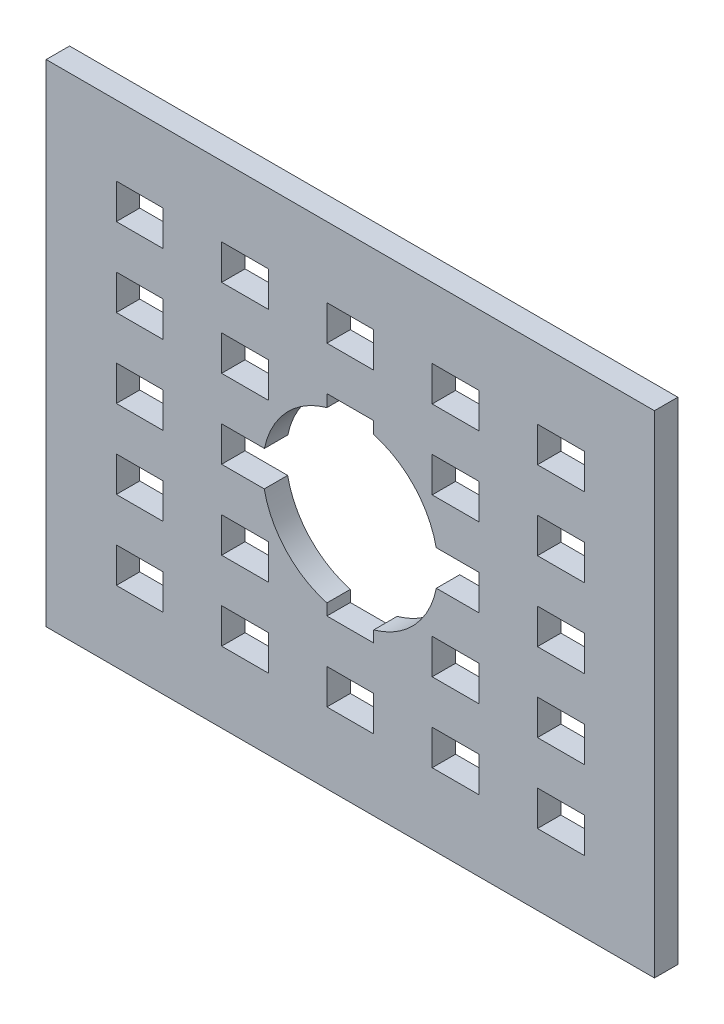
SolidWorks part; units mm, degrees
ref_plane "Front Plane" through (0, 0, 0) normal (0, 0, 1) x (1, 0, 0)
ref_plane "Top Plane" through (0, 0, 0) normal (0, 1, 0) x (1, 0, 0)
ref_plane "Right Plane" through (0, 0, 0) normal (1, 0, 0) x (0, 0, -1)
sketch "Sketch1" plane through (0, 0, 0) normal (0, 1, 0) x (1, 0, 0)
  line L1 (-13, -0.5) -> (13, -0.5)
  line L2 (-13, -0.5) -> (-13, 0.5)
  line L3 (-13, 0.5) -> (13, 0.5)
  line L4 (13, -0.5) -> (13, 0.5)
  line L5 (-13, -0.5) -> (13, 0.5) construction
  line L6 (-13, 0.5) -> (13, -0.5) construction
  point P0 (0, 0)
  dimension "D1" = 26
  dimension "D2" = 1
extrude "Boss-Extrude1" add sketch "Sketch1" along normal blind 21
sketch "Sketch2" plane through (0, 0, 0.5) normal (0, 0, 1) x (1, 0, 0)
  line L0 (-13, 10.5) -> (-10, 10.5) construction
  line L1 (-5.5, 18) -> (-3.5, 18)
  line L2 (-13, 21) -> (-13, 0) construction
  line L3 (0, 21) -> (0, 18) construction
  line L4 (-10, 18) -> (-8, 18)
  line L5 (-13, 21) -> (13, 21) construction
  line L6 (-10, 3) -> (10, 3) construction
  line L7 (-10, 3) -> (-10, 18) construction
  line L8 (-10, 18) -> (10, 18) construction
  line L9 (10, 3) -> (10, 18) construction
  line L10 (-10, 3) -> (10, 18) construction
  line L11 (-10, 18) -> (10, 3) construction
  line L12 (-10, 18) -> (-10, 16.5)
  line L13 (-10, 16.5) -> (-8, 16.5)
  line L14 (-8, 18) -> (-8, 16.5)
  line L15 (-3.5, 18) -> (-3.5, 16.5)
  line L16 (-5.5, 18) -> (-5.5, 16.5)
  line L17 (-5.5, 16.5) -> (-3.5, 16.5)
  line L18 (-1, 18) -> (1, 18)
  line L19 (1, 18) -> (1, 16.5)
  line L20 (-1, 18) -> (-1, 16.5)
  line L21 (-1, 16.5) -> (1, 16.5)
  line L22 (3.5, 18) -> (5.5, 18)
  line L23 (5.5, 18) -> (5.5, 16.5)
  line L24 (3.5, 18) -> (3.5, 16.5)
  line L25 (3.5, 16.5) -> (5.5, 16.5)
  line L26 (8, 18) -> (10, 18)
  line L27 (10, 18) -> (10, 16.5)
  line L28 (8, 18) -> (8, 16.5)
  line L29 (8, 16.5) -> (10, 16.5)
  line L30 (-10, 14.6333) -> (-8, 14.6333)
  line L31 (-10, 14.6333) -> (-10, 13.1333)
  line L32 (-8, 14.6333) -> (-8, 13.1333)
  line L33 (-10, 13.1333) -> (-8, 13.1333)
  line L34 (-5.5, 14.6333) -> (-3.5, 14.6333)
  line L35 (-5.5, 14.6333) -> (-5.5, 13.1333)
  line L36 (-5.5, 13.1333) -> (-3.5, 13.1333)
  line L37 (-3.5, 14.6333) -> (-3.5, 13.1333)
  line L38 (-1, 14.6333) -> (-1, 13.1333)
  line L39 (-1, 14.6333) -> (1, 14.6333)
  line L40 (1, 14.6333) -> (1, 13.1333)
  line L41 (-1, 13.1333) -> (1, 13.1333)
  line L42 (3.5, 14.6333) -> (5.5, 14.6333)
  line L43 (3.5, 14.6333) -> (3.5, 13.1333)
  line L44 (5.5, 14.6333) -> (5.5, 13.1333)
  line L45 (3.5, 13.1333) -> (5.5, 13.1333)
  line L46 (8, 14.6333) -> (10, 14.6333)
  line L47 (8, 14.6333) -> (8, 13.1333)
  line L48 (8, 13.1333) -> (10, 13.1333)
  line L49 (10, 14.6333) -> (10, 13.1333)
  line L50 (-10, 11.2667) -> (-8, 11.2667)
  line L51 (-10, 11.2667) -> (-10, 9.7667)
  line L52 (-8, 11.2667) -> (-8, 9.7667)
  line L53 (-10, 9.7667) -> (-8, 9.7667)
  line L54 (-5.5, 11.2667) -> (-3.5, 11.2667)
  line L55 (-5.5, 11.2667) -> (-5.5, 9.7667)
  line L56 (-5.5, 9.7667) -> (-3.5, 9.7667)
  line L57 (-3.5, 11.2667) -> (-3.5, 9.7667)
  line L58 (-1, 11.2667) -> (-1, 9.7667)
  line L59 (-1, 11.2667) -> (1, 11.2667)
  line L60 (1, 11.2667) -> (1, 9.7667)
  line L61 (-1, 9.7667) -> (1, 9.7667)
  line L62 (3.5, 11.2667) -> (5.5, 11.2667)
  line L63 (3.5, 11.2667) -> (3.5, 9.7667)
  line L64 (5.5, 11.2667) -> (5.5, 9.7667)
  line L65 (3.5, 9.7667) -> (5.5, 9.7667)
  line L66 (8, 11.2667) -> (10, 11.2667)
  line L67 (8, 11.2667) -> (8, 9.7667)
  line L68 (8, 9.7667) -> (10, 9.7667)
  line L69 (10, 11.2667) -> (10, 9.7667)
  line L70 (-10, 7.9) -> (-8, 7.9)
  line L71 (-10, 7.9) -> (-10, 6.4)
  line L72 (-8, 7.9) -> (-8, 6.4)
  line L73 (-10, 6.4) -> (-8, 6.4)
  line L74 (-5.5, 7.9) -> (-3.5, 7.9)
  line L75 (-5.5, 7.9) -> (-5.5, 6.4)
  line L76 (-5.5, 6.4) -> (-3.5, 6.4)
  line L77 (-3.5, 7.9) -> (-3.5, 6.4)
  line L78 (-1, 7.9) -> (-1, 6.4)
  line L79 (-1, 7.9) -> (1, 7.9)
  line L80 (1, 7.9) -> (1, 6.4)
  line L81 (-1, 6.4) -> (1, 6.4)
  line L82 (3.5, 7.9) -> (5.5, 7.9)
  line L83 (3.5, 7.9) -> (3.5, 6.4)
  line L84 (5.5, 7.9) -> (5.5, 6.4)
  line L85 (3.5, 6.4) -> (5.5, 6.4)
  line L86 (8, 7.9) -> (10, 7.9)
  line L87 (8, 7.9) -> (8, 6.4)
  line L88 (8, 6.4) -> (10, 6.4)
  line L89 (10, 7.9) -> (10, 6.4)
  line L90 (-10, 4.5333) -> (-8, 4.5333)
  line L91 (-10, 4.5333) -> (-10, 3.0333)
  line L92 (-8, 4.5333) -> (-8, 3.0333)
  line L93 (-10, 3.0333) -> (-8, 3.0333)
  line L94 (-5.5, 4.5333) -> (-3.5, 4.5333)
  line L95 (-5.5, 4.5333) -> (-5.5, 3.0333)
  line L96 (-5.5, 3.0333) -> (-3.5, 3.0333)
  line L97 (-3.5, 4.5333) -> (-3.5, 3.0333)
  line L98 (-1, 4.5333) -> (-1, 3.0333)
  line L99 (-1, 4.5333) -> (1, 4.5333)
  line L100 (1, 4.5333) -> (1, 3.0333)
  line L101 (-1, 3.0333) -> (1, 3.0333)
  line L102 (3.5, 4.5333) -> (5.5, 4.5333)
  line L103 (3.5, 4.5333) -> (3.5, 3.0333)
  line L104 (5.5, 4.5333) -> (5.5, 3.0333)
  line L105 (3.5, 3.0333) -> (5.5, 3.0333)
  line L106 (8, 4.5333) -> (10, 4.5333)
  line L107 (8, 4.5333) -> (8, 3.0333)
  line L108 (8, 3.0333) -> (10, 3.0333)
  line L109 (10, 4.5333) -> (10, 3.0333)
  point P11 (0, 10.5)
  dimension "D1" = 3
  dimension "D2" = 3
  dimension "D3" = 20
  dimension "D4" = 15
  dimension "D5" = 1.5
  dimension "D6" = 2
  dimension "D7" = 5
extrude "Cut-Extrude1" cut sketch "Sketch2" against normal up to next (1 mm away)
sketch "Sketch3" plane through (0, 0, 0.5) normal (0, 0, 1) x (1, 0, 0)
  line L0 (0, 21) -> (0, 0) construction
  line L1 (-13, 21) -> (13, 21) construction
  line L2 (-13, 0) -> (13, 0) construction
  circle A0 centre (0, 10.5) radius 3.75
extrude "Cut-Extrude3" cut sketch "Sketch3" against normal up to next
